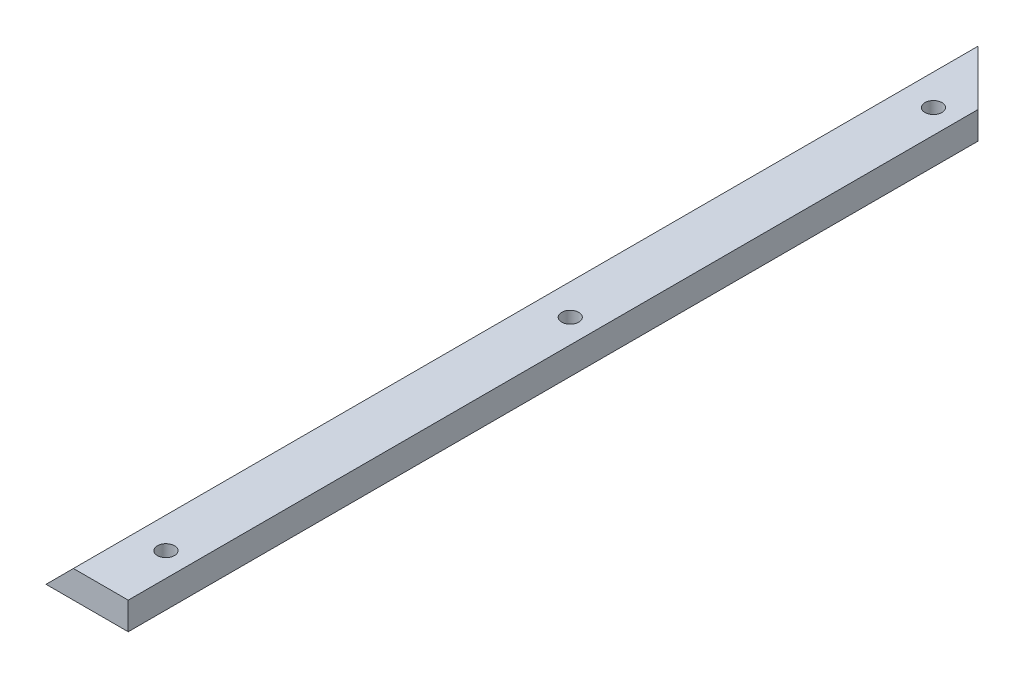
SolidWorks part; units mm, degrees
material "PE High Density"
ref_plane "Front Plane" through (0, 0, 0) normal (0, 0, 1) x (1, 0, 0)
ref_plane "Top Plane" through (0, 0, 0) normal (0, 1, 0) x (1, 0, 0)
ref_plane "Right Plane" through (0, 0, 0) normal (1, 0, 0) x (0, 0, -1)
sketch "Sketch1" plane through (0, 0, 0) normal (0, 0, 1) x (1, 0, 0)
  line L0 (-19.05, -6.35) -> (-6.35, 6.35)
  line L1 (-19.05, -6.35) -> (19.05, -6.35)
  line L3 (-6.35, 6.35) -> (19.05, 6.35)
  line L4 (19.05, -6.35) -> (19.05, 6.35)
  line L5 (-19.05, -6.35) -> (19.05, 6.35) construction
  line L6 (-9.525, 3.175) -> (19.05, -6.35) construction
  point P0 (0, 0)
  dimension "D1" = 38.1
  dimension "D2" = 12.7
  dimension "D3" = 45
extrude "Boss-Extrude1" add sketch "Sketch1" along normal mid plane 431.8
sketch "Sketch2" plane through (0, 6.35, 0) normal (0, 1, 0) x (1, 0, 0)
  line L0 (-19.05, -215.9) -> (-19.05, 215.9) construction
  line L1 (19.05, 215.9) -> (-19.05, 215.9)
  line L2 (19.05, 215.9) -> (19.05, 177.8)
  line L3 (19.05, 177.8) -> (-19.05, 177.8) construction
  line L4 (-19.05, 215.9) -> (-19.05, 177.8) construction
  line L5 (-19.05, 215.9) -> (19.05, 177.8)
  dimension "D1" = 38.1
extrude "Cut-Extrude1" cut sketch "Sketch2" against normal through all
hole_wizard "5/16 (0.3125) Diameter Hole1" positions "Sketch3" profile "Sketch4" hole size "5/16" standard "ANSI Inch" end condition through all
sketch "Sketch3" plane through (0, 6.35, 0) normal (0, 1, 0) x (1, 0, 0)
  line L1 (19.05, -215.9) -> (-6.35, -215.9) construction
  line L3 (19.05, -215.9) -> (19.05, 177.8) construction
  point P8 (7.9375, 0)
  point P10 (7.9375, -187.325)
  point P12 (7.9375, 168.275)
  dimension "D1" = 384.175
  dimension "D2" = 215.9
  dimension "D3" = 28.575
  dimension "D4" = 11.1125
sketch "Sketch4" plane through (7.9375, 6.35, -168.275) normal (1, 0, 0) x (0, 0, 1)
  line L0 (0, 0) -> (0, 12.7)
  line L1 (0, 12.7) -> (3.9687, 12.7)
  line L2 (3.9687, 12.7) -> (3.9687, 0)
  line L5 (3.9687, 0) -> (0, 0)
  line L11 (0, -6.35) -> (0, 107.95) construction
  dimension "Thru Hole Dia." = 7.9375
  dimension "Thru Hole Depth" = 12.7
equation "\"D2@Sketch3\"=17/2"
